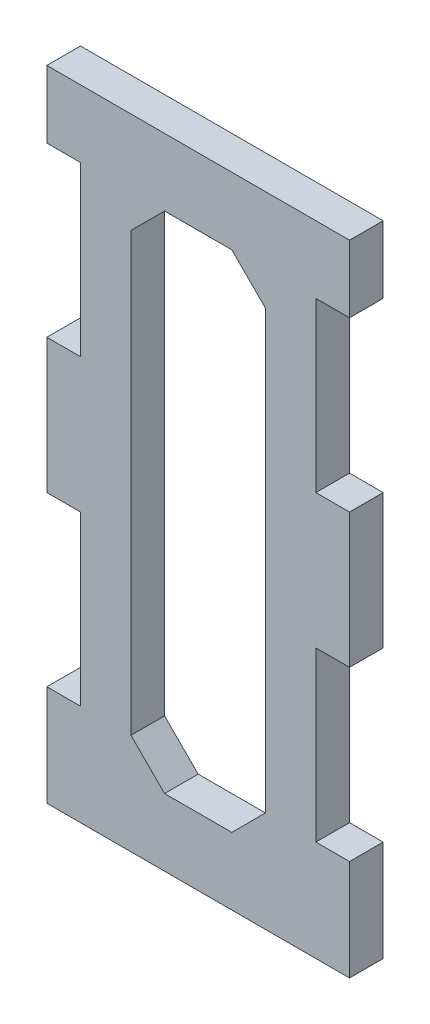
SolidWorks part; units mm, degrees
ref_plane "Plan de face" through (0, 0, 0) normal (0, 0, 1) x (1, 0, 0)
ref_plane "Plan de dessus" through (0, 0, 0) normal (0, 1, 0) x (1, 0, 0)
ref_plane "Plan de droite" through (0, 0, 0) normal (1, 0, 0) x (0, 0, -1)
sketch "Esquisse1" plane through (0, 0, 0) normal (0, 0, 1) x (1, 0, 0)
  line L0 (45, 190) -> (45, 0) construction
  line L1 (0, 0) -> (90, 0)
  line L2 (0, 0) -> (0, 190) construction
  line L3 (0, 190) -> (90, 190)
  line L4 (90, 0) -> (90, 190) construction
  line L5 (0, 0) -> (0, 30)
  line L6 (0, 30) -> (10, 30)
  line L7 (10, 30) -> (10, 80)
  line L8 (10, 80) -> (0, 80)
  line L9 (0, 80) -> (0, 120)
  line L10 (0, 120) -> (10, 120)
  line L11 (10, 120) -> (10, 170)
  line L12 (10, 170) -> (0, 170)
  line L13 (0, 170) -> (0, 190)
  line L14 (10, 170) -> (10, 190) construction
  line L15 (10, 120) -> (10, 80) construction
  line L16 (10, 30) -> (10, 0) construction
  line L17 (90, 0) -> (90, 30)
  line L18 (90, 30) -> (80, 30)
  line L19 (80, 30) -> (80, 80)
  line L20 (80, 80) -> (90, 80)
  line L21 (90, 80) -> (90, 120)
  line L22 (90, 120) -> (80, 120)
  line L23 (80, 120) -> (80, 170)
  line L24 (80, 170) -> (90, 170)
  line L25 (90, 170) -> (90, 190)
  dimension "D1" = 40
  dimension "D2" = 50
  dimension "D3" = 30
  dimension "D4" = 20
  dimension "D5" = 50
  dimension "D6" = 10
  dimension "D7" = 45
extrude "Boss.-Extru.1" add sketch "Esquisse1" along normal blind 10
sketch "Esquisse2" plane through (0, 0, 10) normal (0, 0, 1) x (1, 0, 0)
  line L0 (45, 190) -> (45, 0) construction
  line L1 (90, 190) -> (0, 190) construction
  line L2 (0, 0) -> (90, 0) construction
  line L3 (80, 30) -> (80, 80) construction
  line L4 (35, 170) -> (55, 170)
  line L5 (25, 160) -> (25, 30)
  line L6 (35, 20) -> (55, 20)
  line L7 (65, 160) -> (65, 30)
  line L8 (25, 160) -> (35, 170)
  line L9 (55, 170) -> (65, 160)
  line L10 (55, 20) -> (65, 30)
  line L11 (25, 30) -> (35, 20)
  line L12 (10, 80) -> (10, 30) construction
  point P6 (25, 170)
  point P7 (65, 20)
  point P8 (25, 20)
  point P9 (65, 170)
  dimension "D1" = 20
  dimension "D2" = 20
  dimension "D3" = 15
  dimension "D4" = 15
extrude "Enlèv. mat.-Extru.1" cut sketch "Esquisse2" against normal blind 10
